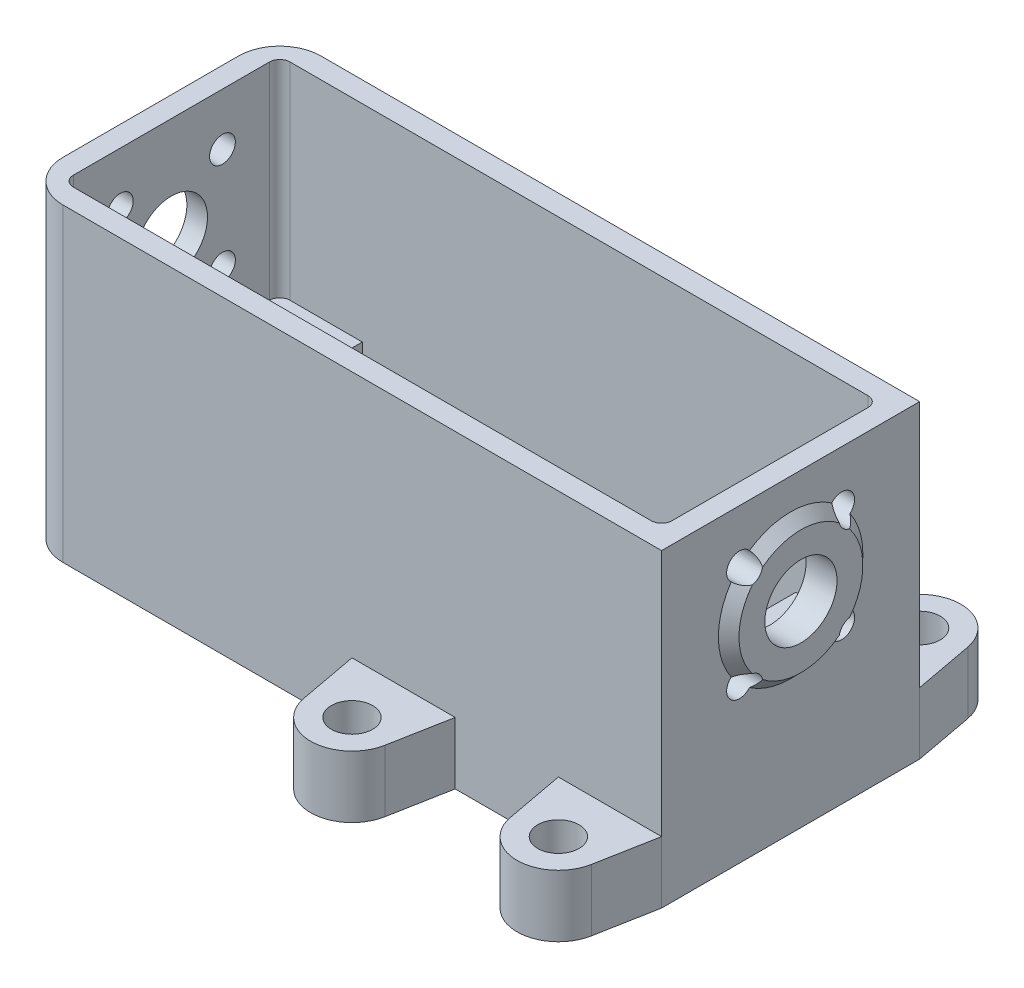
SolidWorks part; units mm, degrees
ref_plane "前视基准面" through (0, 0, 0) normal (0, 0, 1) x (1, 0, 0)
ref_plane "上视基准面" through (0, 0, 0) normal (0, 1, 0) x (1, 0, 0)
ref_plane "右视基准面" through (0, 0, 0) normal (1, 0, 0) x (0, 0, -1)
sketch "草图1" plane through (0, 0, 0) normal (0, 1, 0) x (1, 0, 0)
  line L1 (-31, -12.5) -> (31, -12.5)
  line L2 (-31, -12.5) -> (-31, 12.5)
  line L3 (-31, 12.5) -> (31, 12.5)
  line L4 (31, -12.5) -> (31, 12.5)
  line L5 (-31, -12.5) -> (31, 12.5) construction
  line L6 (-31, 12.5) -> (31, -12.5) construction
  point P0 (0, 0)
  dimension "D1" = 62
  dimension "D2" = 25
extrude "凸台-拉伸1" add sketch "草图1" along normal blind 30
shell "抽壳1" thickness 2
sketch "草图2" plane through (0, 2, 0) normal (0, 1, 0) x (1, 0, 0)
  line L0 (-29, -10.5) -> (29, -10.5) construction
  line L1 (-29, 10.5) -> (-21, 10.5)
  line L2 (-29, 10.5) -> (-29, -10.5)
  line L3 (-29, -10.5) -> (-21, -10.5)
  line L4 (-21, 10.5) -> (-21, -10.5)
  line L5 (29, 10.5) -> (-29, 10.5) construction
  line L6 (21, 10.5) -> (29, 10.5)
  line L7 (21, 10.5) -> (21, -10.5)
  line L8 (21, -10.5) -> (29, -10.5)
  line L9 (29, 10.5) -> (29, -10.5)
  line L10 (29, -10.5) -> (29, 10.5) construction
  line L11 (29, -10.5) -> (29, 10.5) construction
  dimension "D1" = 8
  dimension "D2" = 8
extrude "凸台-拉伸2" add sketch "草图2" along normal blind 8
sketch "草图3" plane through (0, 10, 0) normal (0, 1, 0) x (1, 0, 0)
  line L0 (0, 0) -> (0, 16.0703) construction
  line L1 (29, -10.5) -> (29, 10.5) construction
  line L2 (29, 10.5) -> (21, 10.5) construction
  circle A0 centre (25, -5) radius 2
  circle A1 centre (25, 5) radius 2
  circle A2 centre (-25, 5) radius 2
  circle A3 centre (-25, -5) radius 2
  dimension "D1" = 4
  dimension "D2" = 4
  dimension "D3" = 5.5
  dimension "D4" = 10
extrude "切除-拉伸1" cut sketch "草图3" against normal through all
sketch "草图4" plane through (0, 2, 0) normal (0, 1, 0) x (1, 0, 0)
  line L0 (-21, -10.5) -> (-21, 10.5) construction
  circle A0 centre (-12, 0) radius 6
  dimension "D2" = 12
  dimension "D1" = 9
extrude "切除-拉伸2" cut sketch "草图4" against normal through all
sketch "草图5" plane through (0, 0, 0) normal (0, 1, 0) x (1, 0, 0)
  line L0 (22.0676, 18.2324) -> (21, 12.5)
  line L1 (31, 12.5) -> (-31, 12.5) construction
  line L2 (21, 12.5) -> (31, 12.5)
  line L3 (31, 12.5) -> (29.9324, 18.2324)
  line L4 (26, 17.5) -> (26, 12.5) construction
  line L5 (2.0676, 18.2324) -> (1, 12.5)
  line L6 (11, 12.5) -> (9.9324, 18.2324)
  line L7 (0, 0) -> (31, 0) construction
  line L8 (31, -12.5) -> (31, 12.5) construction
  line L9 (26, -17.5) -> (26, -12.5) construction
  line L10 (11, -12.5) -> (9.9324, -18.2324)
  line L11 (2.0676, -18.2324) -> (1, -12.5)
  line L12 (31, -12.5) -> (29.9324, -18.2324)
  line L13 (21, -12.5) -> (31, -12.5)
  line L14 (22.0676, -18.2324) -> (21, -12.5)
  line L15 (11, 12.5) -> (1, 12.5)
  line L16 (1, -12.5) -> (11, -12.5)
  arc A0 (29.9324, 18.2324) -> (22.0676, 18.2324) centre (26, 17.5) ccw
  circle A1 centre (26, 17.5) radius 2
  circle A2 centre (6, 17.5) radius 2
  arc A3 (9.9324, 18.2324) -> (2.0676, 18.2324) centre (6, 17.5) ccw
  arc A4 (9.9324, -18.2324) -> (2.0676, -18.2324) centre (6, -17.5) cw
  circle A5 centre (6, -17.5) radius 2
  circle A6 centre (26, -17.5) radius 2
  arc A7 (29.9324, -18.2324) -> (22.0676, -18.2324) centre (26, -17.5) cw
  dimension "D2" = 4
  dimension "D3" = 4
  dimension "D4" = 5
  dimension "D1" = 5
  dimension "D6" = 20
  dimension "D5" = 2
extrude "凸台-拉伸3" add sketch "草图5" along normal blind 6
sketch "草图6" plane through (31, 0, 0) normal (1, 0, 0) x (0, 0, -1)
  circle A0 centre (0, 20) radius 7
  dimension "D1" = 20
  dimension "D2" = 14
extrude "凸台-拉伸4" add sketch "草图6" along normal blind 1
sketch "草图7" plane through (0, 0, 0) normal (0, 0, 1) x (1, 0, 0)
  line L0 (31, 27) -> (33, 27)
  line L1 (33, 27) -> (33, 25)
  line L2 (33, 25) -> (31, 27)
  line L3 (31, 30) -> (31, 6) construction
  dimension "D1" = 45
  dimension "D2" = 2
revolve "切除-旋转1" cut sketch "草图7" angle 360 about axis through (32, 20, 0) along (-1, 0, 0)
sketch "草图10" plane through (-31, 0, 0) normal (-1, 0, 0) x (0, 0, 1)
  line L0 (0, 20) -> (0, 30) construction
  line L1 (-12.5, 30) -> (12.5, 30) construction
  line L2 (0, 20) -> (-4.9497, 24.9497) construction
  circle A0 centre (0, 20) radius 3.5
  circle A1 centre (-4.9497, 24.9497) radius 1.25
  circle A2 centre (4.9497, 24.9497) radius 1.25
  circle A3 centre (4.9497, 15.0503) radius 1.25
  circle A4 centre (-4.9497, 15.0503) radius 1.25
  point P17 (0, 20)
  dimension "D1" = 7
  dimension "D4" = 2.5
  dimension "D5" = 20
  dimension "D2" = 45
  dimension "D3" = 7
  dimension "D6" = 4
extrude "切除-拉伸3" cut sketch "草图10" against normal through all
fillet "圆角1" radius 4 2 edges at (-31, 15, -12.5) (-31, 15, 12.5)
fillet "圆角2" radius 1 4 edges at (29, 20, -10.5) (-29, 20, 10.5) (29, 20, 10.5) (-29, 20, -10.5)
move or copy body "实体-移动/复制1" [suppressed] bodies to move or copy 113
